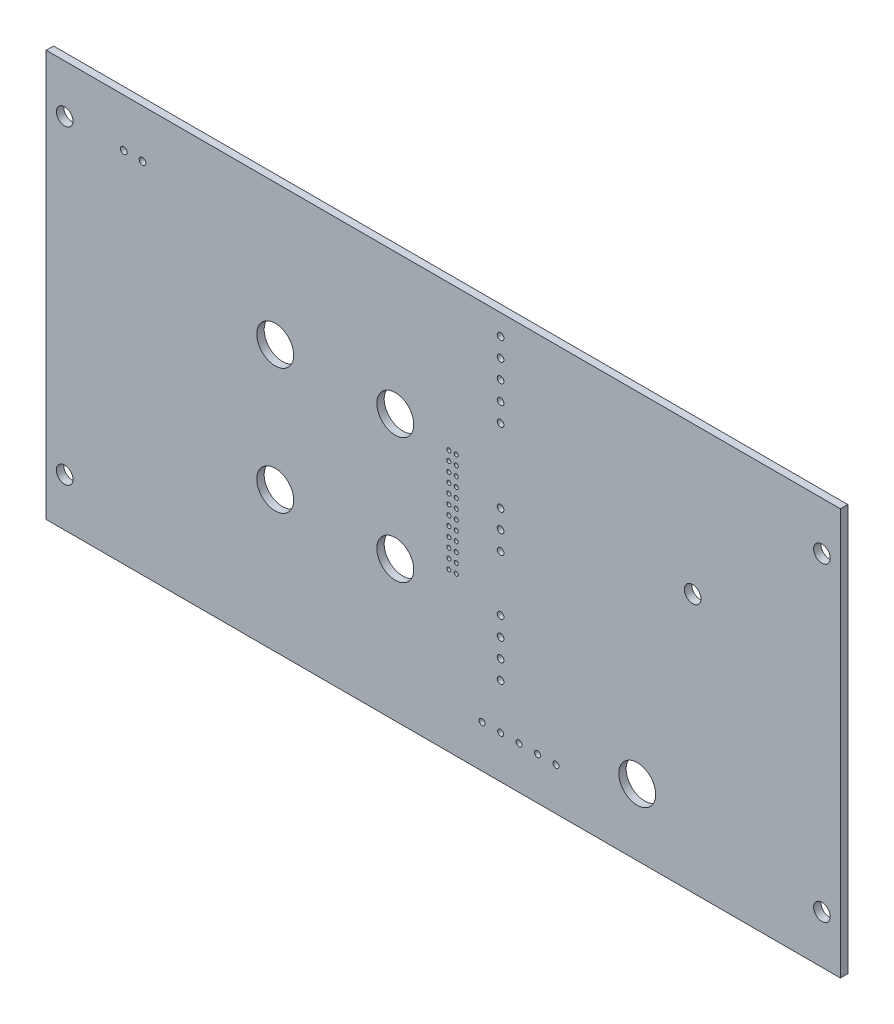
SolidWorks part; units mm, degrees
ref_plane "Спереди" through (0, 0, 0) normal (0, 0, 1) x (1, 0, 0)
ref_plane "Сверху" through (0, 0, 0) normal (0, 1, 0) x (1, 0, 0)
ref_plane "Справа" through (0, 0, 0) normal (1, 0, 0) x (0, 0, -1)
sketch "Эскиз1" plane through (0, 0, 0) normal (0, 0, 1) x (1, 0, 0)
  line L0 (-85.9912, 0) -> (95.9902, 0) construction
  line L1 (0, 50.9948) -> (0, -44.9954) construction
  line L3 (-107.5, -55) -> (107.5, -55)
  line L4 (-107.5, -55) -> (-107.5, 55)
  line L5 (-107.5, 55) -> (107.5, 55)
  line L6 (107.5, -55) -> (107.5, 55)
  circle A0 centre (-102.5, 42) radius 2.25
  circle A1 centre (102.5, 42) radius 2.25
  circle A2 centre (102.5, -42) radius 2.25
  circle A3 centre (-102.5, -42) radius 2.25
  circle A4 centre (-45.5, 17) radius 5
  circle A5 centre (-13, 17) radius 5
  circle A6 centre (-13, -17) radius 5
  circle A7 centre (-45.5, -17) radius 5
  circle A8 centre (52.5, -37) radius 5
  circle A9 centre (67.5, 15) radius 2.25
  dimension "D4" = 13
  dimension "D5" = 4.5
  dimension "D14" = 10
  dimension "D15" = 4.5
  dimension "D16" = 70
  dimension "D17" = 18
  dimension "D1" = 215
  dimension "D2" = 110
  dimension "D3" = 5
  dimension "D6" = 62
  dimension "D7" = 62
  dimension "D8" = 38
  dimension "D9" = 38
  dimension "D10" = 94.5
  dimension "D11" = 94.5
  dimension "D12" = 72
  dimension "D13" = 72
  dimension "D18" = 160
  dimension "D19" = 175
extrude "Вытянуть1" add sketch "Эскиз1" along normal blind 2
sketch "Эскиз3" plane through (0, 0, 2) normal (0, 0, 1) x (1, 0, 0)
  line L0 (-107.5, -55) -> (107.5, -55) construction
  line L1 (-107.5, 55) -> (-107.5, -55) construction
  circle A0 centre (1.5, 15.72) radius 0.55
  dimension "D1" = 1.1
  dimension "D2" = 70.72
  dimension "D3" = 109
extrude "Вырез-Вытянуть1" cut sketch "Эскиз3" against normal blind 2
pattern_linear "Линейный массив1" count 2 spacing 2 count 12 spacing 2.54
sketch "Эскиз4" plane through (0, 0, 2) normal (0, 0, 1) x (1, 0, 0)
  line L0 (-107.5, 55) -> (-107.5, -55) construction
  line L1 (-107.5, -55) -> (107.5, -55) construction
  line L2 (15.5, 49.4) -> (15.5, -28.6617) construction
  line L3 (-86.5411, 42) -> (-52.0883, 42) construction
  line L4 (5.781, -43.5) -> (35.219, -43.5) construction
  circle A0 centre (15.5, 49.4) radius 0.9
  circle A1 centre (15.5, 44.32) radius 0.9
  circle A2 centre (15.5, 39.24) radius 0.9
  circle A3 centre (15.5, 34.16) radius 0.9
  circle A4 centre (15.5, 29.08) radius 0.9
  circle A5 centre (15.5, -16) radius 0.9
  circle A6 centre (15.5, 9.16) radius 0.9
  circle A7 centre (15.5, 4.08) radius 0.9
  circle A8 centre (15.5, -1) radius 0.9
  circle A9 centre (15.5, -31.24) radius 0.9
  circle A10 centre (15.5, -21.08) radius 0.9
  circle A11 centre (15.5, -26.16) radius 0.9
  circle A12 centre (-86.5, 42) radius 0.9
  circle A13 centre (-81.42, 42) radius 0.9
  circle A14 centre (10.5, -43.5) radius 0.8
  circle A15 centre (15.5, -43.5) radius 0.8
  circle A16 centre (20.5, -43.5) radius 0.8
  circle A17 centre (25.5, -43.5) radius 0.8
  circle A18 centre (30.5, -43.5) radius 0.8
  dimension "D3" = 1.8
  dimension "D6" = 5.08
  dimension "D7" = 5.08
  dimension "D8" = 5.08
  dimension "D9" = 5.08
  dimension "D10" = 5.08
  dimension "D11" = 5.08
  dimension "D14" = 1.8
  dimension "D15" = 1.8
  dimension "D18" = 1.6
  dimension "D19" = 5
  dimension "D20" = 5
  dimension "D21" = 5
  dimension "D22" = 5
  dimension "D1" = 123
  dimension "D2" = 104.4
  dimension "D4" = 64.16
  dimension "D5" = 39
  dimension "D12" = 97
  dimension "D13" = 21
  dimension "D16" = 11.5
  dimension "D17" = 118
extrude "Вырез-Вытянуть2" cut sketch "Эскиз4" against normal blind 2
